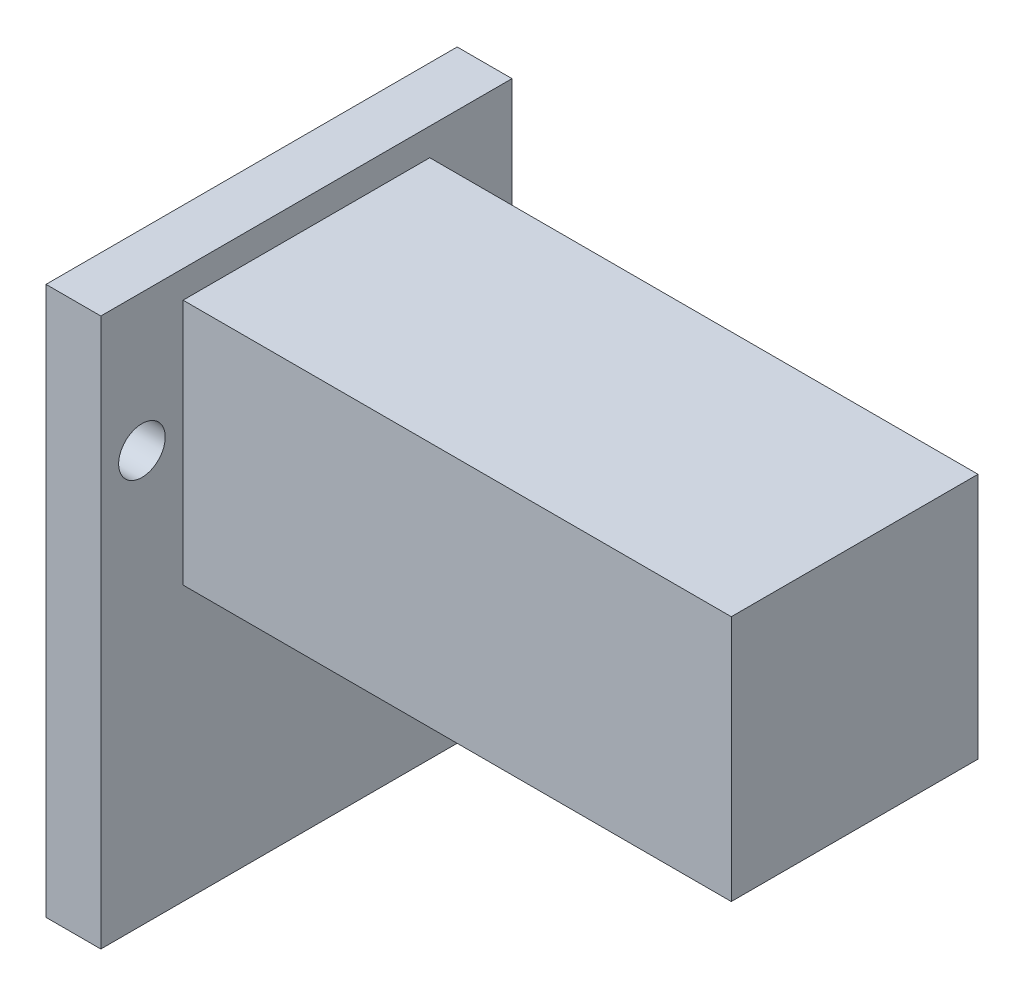
SolidWorks part; units mm, degrees
material "PET"
ref_plane "Front Plane" through (0, 0, 0) normal (0, 0, 1) x (1, 0, 0)
ref_plane "Top Plane" through (0, 0, 0) normal (0, 1, 0) x (1, 0, 0)
ref_plane "Right Plane" through (0, 0, 0) normal (1, 0, 0) x (0, 0, -1)
sketch "Sketch1" plane through (0, 0, 0) normal (1, 0, 0) x (0, 0, -1)
  line L1 (-10.4167, 13.125) -> (19.5833, 13.125)
  line L2 (-10.4167, 13.125) -> (-10.4167, -26.875)
  line L3 (-10.4167, -26.875) -> (19.5833, -26.875)
  line L4 (19.5833, 13.125) -> (19.5833, -26.875)
  dimension "D1" = 30
  dimension "D2" = 40
extrude "Boss-Extrude1" add sketch "Sketch1" along normal blind 4
sketch "Sketch2" plane through (4, 0, 0) normal (1, 0, 0) x (0, 0, -1)
  line L0 (-10.4167, 13.125) -> (-10.4167, -26.875) construction
  line L1 (-4.4167, 11.125) -> (13.5833, 11.125)
  line L2 (-4.4167, 11.125) -> (-4.4167, -6.875)
  line L3 (-4.4167, -6.875) -> (13.5833, -6.875)
  line L4 (13.5833, 11.125) -> (13.5833, -6.875)
  line L5 (-10.4167, -26.875) -> (19.5833, -26.875) construction
  dimension "D1" = 6
  dimension "D2" = 20
  dimension "D3" = 18
  dimension "D4" = 18
extrude "Boss-Extrude2" add sketch "Sketch2" along normal blind 40
sketch "Sketch3" plane through (4, 0, 0) normal (1, 0, 0) x (0, 0, -1)
  line L1 (-10.4167, 13.125) -> (-10.4167, -26.875) construction
  line L2 (19.5833, -26.875) -> (19.5833, 13.125) construction
  line L3 (19.5833, 13.125) -> (-10.4167, 13.125) construction
  circle A0 centre (-7.4167, 3.125) radius 1.7
  circle A1 centre (16.5833, 3.125) radius 1.7
  dimension "D1" = 3.4
  dimension "D3" = 3.4
  dimension "D4" = 3
  dimension "D5" = 10
  dimension "D6" = 10
  dimension "D2" = 3
extrude "Cut-Extrude1" cut sketch "Sketch3" against normal through all
